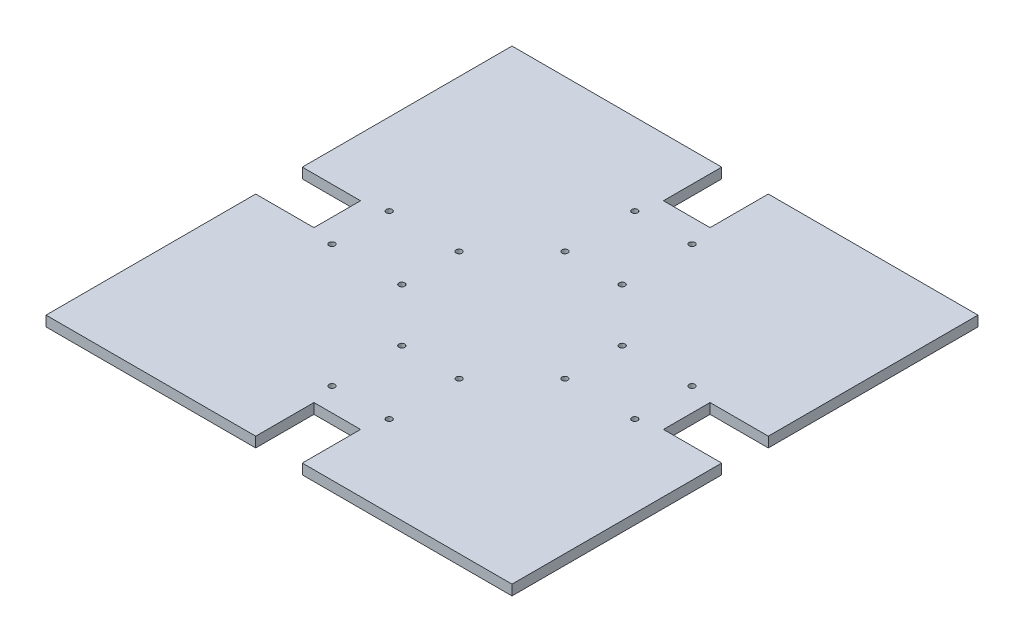
SolidWorks part; units mm, degrees
ref_plane "Front Plane" through (0, 0, 0) normal (0, 0, 1) x (1, 0, 0)
ref_plane "Top Plane" through (0, 0, 0) normal (0, 1, 0) x (1, 0, 0)
ref_plane "Right Plane" through (0, 0, 0) normal (1, 0, 0) x (0, 0, -1)
sketch "Sketch1" plane through (0, 0, 0) normal (0, 1, 0) x (1, 0, 0)
  line L0 (0, 127) -> (127, 0) construction
  line L1 (-127, 127) -> (127, 127)
  line L2 (-127, 127) -> (-127, -127)
  line L3 (-127, -127) -> (127, -127)
  line L4 (127, 127) -> (127, -127)
  line L5 (-127, 127) -> (127, -127) construction
  line L6 (-127, -127) -> (127, 127) construction
  line L7 (127, 0) -> (0, -127) construction
  line L8 (0, -127) -> (-127, 0) construction
  line L9 (-127, 0) -> (0, 127) construction
  point P0 (0, 0)
  dimension "D1" = 254
  dimension "D2" = 254
  dimension "D3" = 179.6051
extrude "Boss-Extrude1" add sketch "Sketch1" along normal blind 5.588
sketch "Sketch2" plane through (0, 5.588, 0) normal (0, 1, 0) x (1, 0, 0)
  line L0 (0, 127) -> (0, -127) construction
  line L1 (-82.55, 15.6) -> (-44.45, 15.6) construction
  line L2 (-82.55, 15.6) -> (-82.55, -15.6) construction
  line L3 (-82.55, -15.6) -> (-44.45, -15.6) construction
  line L4 (-44.45, 15.6) -> (-44.45, -15.6) construction
  line L5 (-82.55, 15.6) -> (-44.45, -15.6) construction
  line L6 (-82.55, -15.6) -> (-44.45, 15.6) construction
  line L7 (-15.6, 82.55) -> (15.6, 82.55) construction
  line L8 (-15.6, 82.55) -> (-15.6, 44.45) construction
  line L9 (-15.6, 44.45) -> (15.6, 44.45) construction
  line L10 (15.6, 82.55) -> (15.6, 44.45) construction
  line L11 (-15.6, 82.55) -> (15.6, 44.45) construction
  line L12 (-15.6, 44.45) -> (15.6, 82.55) construction
  line L13 (-15.6, -44.45) -> (15.6, -44.45) construction
  line L14 (-15.6, -44.45) -> (-15.6, -82.55) construction
  line L15 (-15.6, -82.55) -> (15.6, -82.55) construction
  line L16 (15.6, -44.45) -> (15.6, -82.55) construction
  line L17 (-15.6, -44.45) -> (15.6, -82.55) construction
  line L18 (-15.6, -82.55) -> (15.6, -44.45) construction
  line L19 (44.45, 15.6) -> (82.55, 15.6) construction
  line L20 (44.45, 15.6) -> (44.45, -15.6) construction
  line L21 (44.45, -15.6) -> (82.55, -15.6) construction
  line L22 (82.55, 15.6) -> (82.55, -15.6) construction
  line L23 (44.45, 15.6) -> (82.55, -15.6) construction
  line L24 (44.45, -15.6) -> (82.55, 15.6) construction
  line L25 (127, 127) -> (-127, 127) construction
  line L26 (-127, -127) -> (127, -127) construction
  line L28 (-127, 127) -> (-127, -127) construction
  line L29 (-127, 0) -> (127, 0) construction
  line L30 (127, -127) -> (127, 127) construction
  line L31 (-127, -12.7) -> (-95.25, -12.7)
  line L32 (-127, -12.7) -> (-127, 12.7)
  line L33 (-127, 12.7) -> (-95.25, 12.7)
  line L34 (-95.25, -12.7) -> (-95.25, 12.7)
  line L35 (-127, -12.7) -> (-95.25, 12.7) construction
  line L36 (-127, 12.7) -> (-95.25, -12.7) construction
  line L37 (-12.7, 95.25) -> (12.7, 95.25)
  line L38 (-12.7, 95.25) -> (-12.7, 127)
  line L39 (-12.7, 127) -> (12.7, 127)
  line L40 (12.7, 95.25) -> (12.7, 127)
  line L41 (-12.7, 95.25) -> (12.7, 127) construction
  line L42 (-12.7, 127) -> (12.7, 95.25) construction
  line L43 (95.25, -12.7) -> (127, -12.7)
  line L44 (95.25, -12.7) -> (95.25, 12.7)
  line L45 (95.25, 12.7) -> (127, 12.7)
  line L46 (127, -12.7) -> (127, 12.7)
  line L47 (95.25, -12.7) -> (127, 12.7) construction
  line L48 (95.25, 12.7) -> (127, -12.7) construction
  line L49 (-12.7, -127) -> (12.7, -127)
  line L50 (-12.7, -127) -> (-12.7, -95.25)
  line L51 (-12.7, -95.25) -> (12.7, -95.25)
  line L52 (12.7, -127) -> (12.7, -95.25)
  line L53 (-12.7, -127) -> (12.7, -95.25) construction
  line L54 (-12.7, -95.25) -> (12.7, -127) construction
  circle A0 centre (-82.55, 15.6) radius 1.6
  circle A1 centre (-44.45, 15.6) radius 1.6
  circle A2 centre (-82.55, -15.6) radius 1.6
  circle A3 centre (-44.45, -15.6) radius 1.6
  circle A4 centre (-15.6, -44.45) radius 1.6
  circle A5 centre (15.6, -44.45) radius 1.6
  circle A6 centre (-15.6, -82.55) radius 1.6
  circle A7 centre (15.6, -82.55) radius 1.6
  circle A8 centre (44.45, -15.6) radius 1.6
  circle A9 centre (44.45, 15.6) radius 1.6
  circle A10 centre (82.55, 15.6) radius 1.6
  circle A11 centre (82.55, -15.6) radius 1.6
  circle A12 centre (-15.6, 44.45) radius 1.6
  circle A13 centre (-15.6, 82.55) radius 1.6
  circle A14 centre (15.6, 82.55) radius 1.6
  circle A15 centre (15.6, 44.45) radius 1.6
  point P0 (-63.5, 0)
  point P5 (0, 63.5)
  point P10 (0, -63.5)
  point P15 (63.5, 0)
  point P48 (-111.125, 0)
  point P53 (0, 111.125)
  point P58 (111.125, 0)
  point P63 (0, -111.125)
  dimension "D1" = 3.2
  dimension "D2" = 38.1
  dimension "D3" = 31.2
  dimension "D4" = 25.4
  dimension "D5" = 31.75
extrude "Cut-Extrude1" cut sketch "Sketch2" against normal through all
